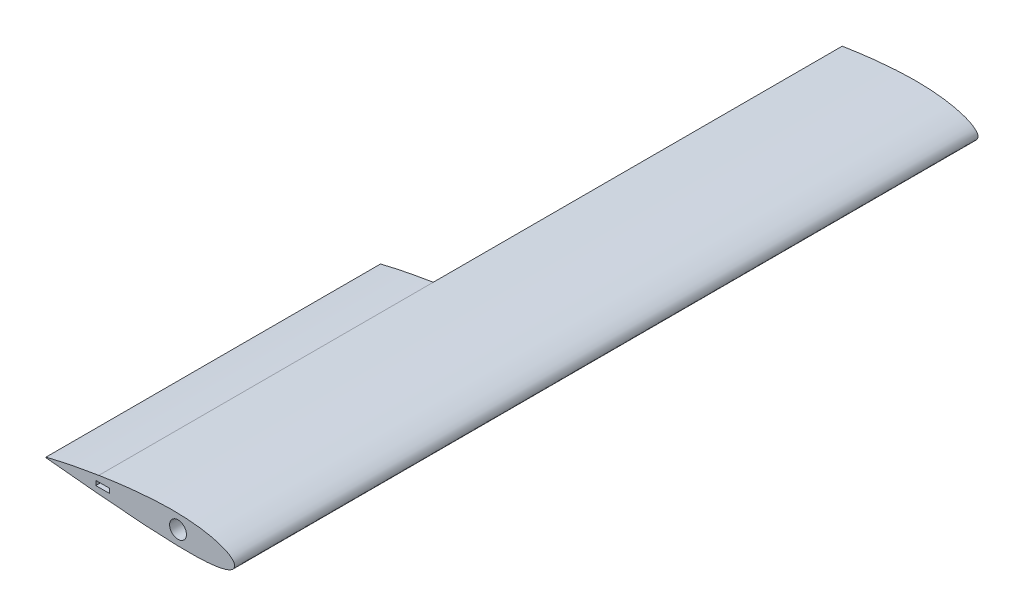
SolidWorks part; units mm, degrees
ref_plane "Front Plane" through (0, 0, 0) normal (0, 0, 1) x (1, 0, 0)
ref_plane "Top Plane" through (0, 0, 0) normal (0, 1, 0) x (1, 0, 0)
ref_plane "Right Plane" through (0, 0, 0) normal (1, 0, 0) x (0, 0, -1)
sketch "Sketch1" plane through (0, 0, 0) normal (0, 0, 1) x (1, 0, 0)
  line L0 (-204.6067, 16.4337) -> (-204.6067, -8.1987)
  spline S0 degree 3 poles (-204.6067, 16.4337) (-202.0364, 16.8435) (-195.9768, 17.8096) (-186.3199, 19.2196) (-175.5722, 20.6819) (-164.6073, 22.0386) (-153.494, 23.2716) (-142.3015, 24.3576) (-131.0997, 25.2761) (-119.9435, 26.0067) (-108.8824, 26.5372) (-97.9847, 26.7846) (-87.3392, 26.7465) (-77.0378, 26.4169) (-67.1496, 25.7985) (-57.7411, 24.8989) (-48.875, 23.7311) (-40.6098, 22.3135) (-32.999, 20.6688) (-26.0908, 18.8238) (-19.9273, 16.8078) (-14.5439, 14.6516) (-9.9686, 12.3852) (-6.2214, 10.0358) (-3.3137, 7.6219) (-1.2528, 5.1467) (-0.0675, 2.5867) (0.1546, -0.0155) (-0.5776, -2.5202) (-2.2311, -4.7957) (-4.7051, -6.8272) (-7.9698, -8.6527) (-12.012, -10.2839) (-16.8128, -11.7212) (-22.346, -12.9608) (-28.5794, -13.9994) (-35.4759, -14.8356) (-42.995, -15.4709) (-51.093, -15.9105) (-59.7234, -16.1628) (-68.8374, -16.2403) (-78.3839, -16.1585) (-88.3098, -15.9358) (-98.5596, -15.5937) (-109.0967, -15.1513) (-119.8773, -14.6385) (-130.8353, -14.0093) (-141.8845, -13.2901) (-152.9424, -12.4996) (-163.9423, -11.6567) (-174.817, -10.7785) (-185.4999, -9.8796) (-195.4089, -9.0211) (-201.7486, -8.4543) (-204.6067, -8.1987) knots 0 0 0 0 0.018424 0.043434 0.06908 0.095203 0.12164 0.148227 0.1748 0.201195 0.227364 0.253182 0.278347 0.30271 0.326128 0.348467 0.3696 0.389416 0.407811 0.424699 0.440008 0.453688 0.465715 0.476104 0.484928 0.49236 0.49873 0.504587 0.510443 0.516804 0.524199 0.532941 0.543186 0.554996 0.568376 0.583299 0.599709 0.617539 0.636704 0.657109 0.678651 0.701217 0.724685 0.748928 0.773811 0.799338 0.825326 0.851504 0.877716 0.9038 0.929596 0.954944 0.979688 1 1 1 1
extrude "Boss-Extrude1" add sketch "Sketch1" against normal blind 1120
sketch "Sketch2" plane through (0, 0, 0) normal (0, 0, 1) x (1, 0, 0)
  line L0 (-204.6067, 16.4337) -> (-204.6067, -8.1987)
  line L1 (-284.176, 0.4539) -> (-284.176, -0.4466)
  spline S0 degree 3 poles (-204.6067, 16.4337) (-205.4155, 16.3071) (-209.473, 15.6715) (-216.6128, 14.4575) (-225.8556, 12.8273) (-234.5737, 11.204) (-242.7164, 9.6201) (-250.2346, 8.0967) (-257.084, 6.6573) (-263.2241, 5.3239) (-268.6191, 4.1181) (-273.2376, 3.0598) (-277.0529, 2.1669) (-280.0432, 1.4552) (-282.1913, 0.9372) (-283.4751, 0.6251) (-284.0416, 0.4867) (-284.176, 0.4539) knots 0 0 0 0 0.030252 0.151774 0.267626 0.37709 0.479485 0.574175 0.66057 0.73813 0.806369 0.864859 0.913229 0.951173 0.978451 0.994887 1 1 1 1
  spline S1 degree 3 poles (-204.6067, -8.1987) (-205.1233, -8.1528) (-208.8868, -7.8183) (-215.7471, -7.1903) (-225.0196, -6.3324) (-233.7877, -5.5056) (-241.996, -4.7193) (-249.5923, -3.9801) (-256.5279, -3.2948) (-262.7581, -2.6701) (-268.2426, -2.1118) (-272.9458, -1.6282) (-276.8367, -1.2191) (-279.8905, -0.906) (-282.085, -0.6533) (-283.41, -0.5467) (-284.0076, -0.446) (-284.1661, -0.4466) (-284.176, -0.4466) knots 0 0 0 0 0.019463 0.141781 0.258505 0.3689 0.472262 0.567931 0.655294 0.733785 0.802892 0.862162 0.911205 0.949694 0.977373 0.994054 0.999628 1 1 1 1
extrude "Boss-Extrude2" add sketch "Sketch2" against normal blind 504
sketch "Sketch3" plane through (0, 0, 0) normal (0, 0, 1) x (1, 0, 0)
  circle A0 centre (-85.253, 5.328) radius 12.7
extrude "Cut-Extrude1" cut sketch "Sketch3" against normal blind 801
ref_plane "Plane1" through (0, 0, -376.7) normal (0, 0, 1) x (1, 0, 0)
sketch "Sketch4" plane through (0, 0, -376.7) normal (0, 0, 1) x (1, 0, 0)
  line L0 (-101.253, -16.991) -> (-69.253, -16.991)
  line L1 (-69.253, -16.991) -> (-69.253, 21.028)
  line L2 (-69.253, 21.028) -> (-101.253, 21.028)
  line L3 (-101.253, 21.028) -> (-101.253, -16.991)
extrude "Cut-Extrude2" cut sketch "Sketch4" along normal blind 46
ref_plane "Plane2" through (0, 0, -376.7) normal (0, 0, 1) x (1, 0, 0)
sketch "Sketch5" plane through (0, 0, -376.7) normal (0, 0, 1) x (1, 0, 0)
  line L0 (-257.3408, -8.16) -> (-197.3408, -8.16)
  line L1 (-197.3408, -8.16) -> (-197.3408, 3.84)
  line L2 (-197.3408, 3.84) -> (-257.3408, 3.84)
  line L3 (-257.3408, 3.84) -> (-257.3408, -8.16)
extrude "Cut-Extrude3" cut sketch "Sketch5" along normal blind 46
ref_plane "Plane3" through (0, 0, -598.5) normal (0, 0, 1) x (1, 0, 0)
sketch "Sketch6" plane through (0, 0, -598.5) normal (0, 0, 1) x (1, 0, 0)
  line L0 (-183.297, -15.264) -> (-129.297, -15.264)
  line L1 (-129.297, -15.264) -> (-129.297, 13.836)
  line L2 (-129.297, 13.836) -> (-183.297, 13.836)
  line L3 (-183.297, 13.836) -> (-183.297, -15.264)
extrude "Cut-Extrude4" cut sketch "Sketch6" along normal blind 64
ref_plane "Plane4" through (0, 0, -25.5) normal (0, 0, 1) x (1, 0, 0)
sketch "Sketch7" plane through (0, 0, -25.5) normal (0, 0, 1) x (1, 0, 0)
  line L0 (-209.123, 0.863) -> (-188.723, 0.863)
  line L1 (-188.723, 0.863) -> (-188.723, 7.663)
  line L2 (-188.723, 7.663) -> (-209.123, 7.663)
  line L3 (-209.123, 7.663) -> (-209.123, 0.863)
extrude "Cut-Extrude5" cut sketch "Sketch7" along normal blind 26
ref_plane "Plane5" through (0, 0, -930) normal (0, 0, 1) x (1, 0, 0)
sketch "Sketch8" plane through (0, 0, -930) normal (0, 0, 1) x (1, 0, 0)
  line L0 (-60, -17.172) -> (-40, -17.172)
  line L1 (-40, -17.172) -> (-40, -13.172)
  line L2 (-40, -13.172) -> (-60, -13.172)
  line L3 (-60, -13.172) -> (-60, -17.172)
extrude "Cut-Extrude6" cut sketch "Sketch8" along normal blind 20
